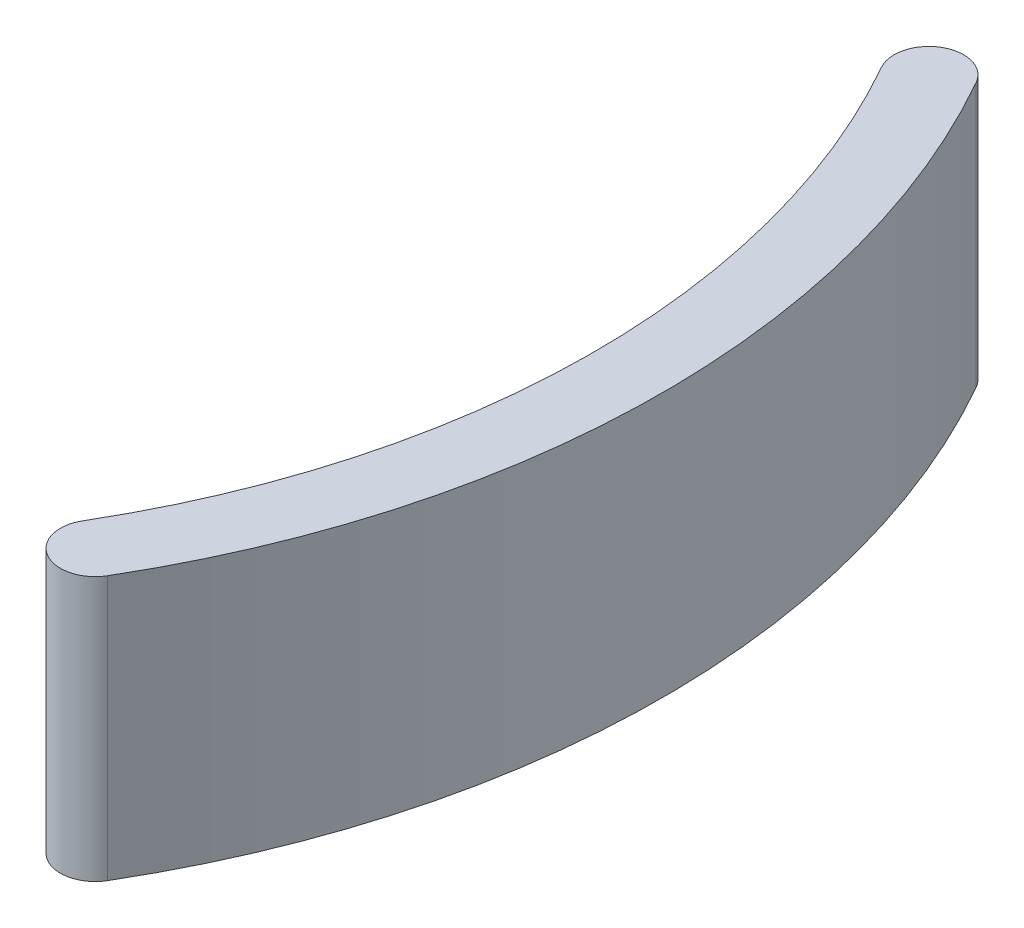
SolidWorks part; units mm, degrees
ref_plane "Alzado" through (0, 0, 0) normal (0, 0, 1) x (1, 0, 0)
ref_plane "Planta" through (0, 0, 0) normal (0, 1, 0) x (1, 0, 0)
ref_plane "Vista lateral" through (0, 0, 0) normal (1, 0, 0) x (0, 0, -1)
sketch "Sketch1" plane through (0, 0, 0) normal (0, 1, 0) x (1, 0, 0)
  line L0 (-16.431, -59.3671) -> (-118.996, 0.9771) construction
  line L1 (-118.996, 0.9771) -> (-15.4539, 59.6289) construction
  line L2 (-118.996, 0.9771) -> (0, 0) construction
  arc A0 (-16.431, -59.3671) -> (-15.4539, 59.6289) centre (-118.996, 0.9771) ccw construction
  arc A1 (-12.1216, -61.9026) -> (-11.1034, 62.0933) centre (-118.996, 0.9771) ccw
  arc A2 (-20.7405, -56.8316) -> (-19.8044, 57.1645) centre (-118.996, 0.9771) ccw
  arc A3 (-20.7405, -56.8316) -> (-12.1216, -61.9026) centre (-16.431, -59.3671) ccw
  arc A4 (-11.1034, 62.0933) -> (-19.8044, 57.1645) centre (-15.4539, 59.6289) ccw
  point P4 (0, 0)
  point P18 (0, 0)
  dimension "D1" = 124
  dimension "D2" = 5
  dimension "D3" = 60
extrude "Boss-Extrude1" add sketch "Sketch1" along normal blind 38 contours A1 A4 A2 A3
